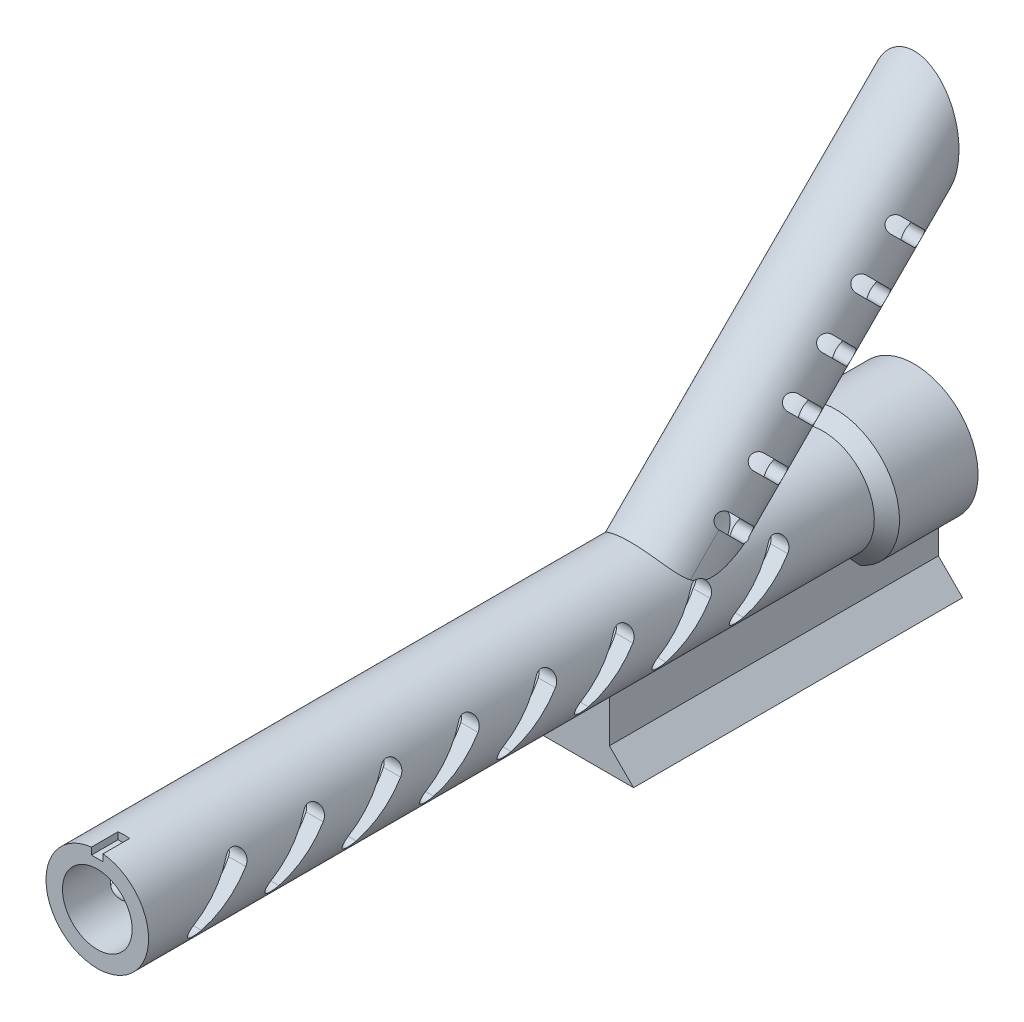
SolidWorks part; units mm, degrees
ref_plane "Front Plane" through (0, 0, 0) normal (0, 0, 1) x (1, 0, 0)
ref_plane "Top Plane" through (0, 0, 0) normal (0, 1, 0) x (1, 0, 0)
ref_plane "Right Plane" through (0, 0, 0) normal (1, 0, 0) x (0, 0, -1)
sketch "Esquisse3" plane through (0, 0, 0) normal (1, 0, 0) x (0, 0, -1)
  line L0 (-115.2452, 0) -> (50.9996, 0) construction
  line L1 (-0.8426, 10.6) -> (-150.8426, 10.6)
  line L2 (0, 7.2) -> (-150.8426, 7.2)
  line L3 (-150.8426, 10.6) -> (-150.8426, 7.2)
  line L4 (-0.8426, 10.6) -> (1.7574, 13.2)
  line L5 (0, 7.2) -> (3, 10.2)
  line L6 (1.7574, 13.2) -> (18, 13.2)
  line L7 (3, 10.2) -> (18, 10.2)
  line L8 (18, 13.2) -> (18, 10.2)
  dimension "D1" = 21.2
  dimension "D2" = 150
  dimension "D3" = 3
  dimension "D4" = 3
  dimension "D5" = 45
  dimension "D6" = 15
  dimension "D7" = 14.4
  dimension "D8" = 20.4
revolve "Révolution2" add sketch "Esquisse3" angle 360 about L0
sketch "Esquisse11" plane through (0, 0, 0) normal (1, 0, 0) x (0, 0, -1)
  line L0 (-27.5426, 10.6) -> (18.4193, 56.5619) construction
  line L1 (-0.8426, 10.6) -> (-150.8426, 10.6) construction
  dimension "D1" = 45
  dimension "D2" = 26.7
  dimension "D3" = 65
ref_plane "Plan1" through (0, 9, -9) normal (0, 0.7071, -0.7071) x (-1, 0, 0)
sketch "Esquisse12" plane through (0, 9, -9) normal (0, 0.7071, -0.7071) x (-1, 0, 0)
  circle A1 centre (0, 26.9709) radius 9.25
  dimension "D1" = 18.5
extrude "Boss.-Extru.2" add sketch "Esquisse12" against normal up to surface and the other way up to surface up to face at (10.6, 0, 150.8426) other way up to face at (13.2, 0, -18)
sketch "Esquisse16" plane through (0, 9, -9) normal (0, 0.7071, -0.7071) x (-1, 0, 0)
  circle A0 centre (0, 26.9709) radius 6.75
  circle A1 centre (0, 26.9709) radius 9.25 construction
  dimension "D1" = 2.5
extrude "Enlèv. mat.-Extru.4" cut sketch "Esquisse16" against normal up to next and the other way up to next
sketch "Esquisse4" plane through (0, 0, 0) normal (1, 0, 0) x (0, 0, -1)
  line L0 (-139.8426, -4) -> (-131.8426, 4) construction
  line L1 (-141.2569, -2.5858) -> (-133.2569, 5.4142)
  line L2 (-138.4284, -5.4142) -> (-130.4284, 2.5858)
  line L3 (-150.8426, 10.6) -> (-150.8426, -10.6) construction
  line L4 (-150.8426, -10.6) -> (-0.8426, -10.6) construction
  arc A0 (-141.2569, -2.5858) -> (-138.4284, -5.4142) centre (-139.8426, -4) ccw
  arc A1 (-130.4284, 2.5858) -> (-133.2569, 5.4142) centre (-131.8426, 4) ccw
  point P2 (-135.8426, 0)
  dimension "D1" = 8
  dimension "D2" = 45
  dimension "D3" = 4
  dimension "D4" = 15
extrude "Enlèv. mat.-Extru.1" cut sketch "Esquisse4" against normal through all both and the other way through all
pattern_linear "Répétition linéaire1" count 8 spacing 16 along (0, 0, -1) of "Enlèv. mat.-Extru.1"
sketch "Esquisse5" plane through (0, 0, 150.8426) normal (0, 0, 1) x (1, 0, 0)
  line L1 (1.2, 10.6) -> (-1.2, 10.6)
  line L2 (1.2, 10.6) -> (1.2, 9.1)
  line L3 (1.2, 9.1) -> (-1.2, 9.1)
  line L4 (-1.2, 10.6) -> (-1.2, 9.1)
  line L5 (1.2, 10.6) -> (-1.2, 9.1) construction
  line L6 (1.2, 9.1) -> (-1.2, 10.6) construction
  line L7 (-1, 9.3) -> (-1, 10.7536) construction
  line L8 (1, 9.3) -> (-1, 9.3) construction
  circle A0 centre (0, 0) radius 10.6 construction
  point P0 (0, 9.85)
  dimension "D1" = 0.2
  dimension "D2" = 0.2
extrude "Enlèv. mat.-Extru.2" cut sketch "Esquisse5" against normal blind 5.5
sketch "Esquisse13" plane through (0, 0, 0) normal (1, 0, 0) x (0, 0, -1)
  line L0 (10.4749, 43.6678) -> (5.5251, 48.6175) construction
  line L1 (9.4142, 42.6071) -> (4.4645, 47.5569)
  line L2 (11.5355, 44.7284) -> (6.5858, 49.6782)
  line L4 (-27.5426, 10.6) -> (18.4193, 56.5619) construction
  line L5 (18, 43.0612) -> (18, 69.2241) construction
  arc A0 (9.4142, 42.6071) -> (11.5355, 44.7284) centre (10.4749, 43.6678) ccw
  arc A1 (6.5858, 49.6782) -> (4.4645, 47.5569) centre (5.5251, 48.6175) ccw
  point P2 (8, 46.1426)
  dimension "D1" = 3
  dimension "D2" = 7
  dimension "D3" = 10
extrude "Enlèv. mat.-Extru.3" cut sketch "Esquisse13" against normal through all both and the other way through all
pattern_linear "Répétition linéaire2" count 6 spacing 10 along (0, -0.7071, 0.7071) of "Enlèv. mat.-Extru.3"
sketch "Esquisse14" plane through (0, 0, 0) normal (0, 0, -1) x (-1, 0, 0)
  line L0 (-5, -18.6603) -> (-10, -23.6603)
  line L1 (-10, -23.6603) -> (10, -23.6603)
  line L2 (10, -23.6603) -> (5, -18.6603)
  line L5 (-5, -18.6603) -> (-5, -9.3467)
  line L6 (5, -18.6603) -> (5, -9.3467)
  arc A1 (5, -9.3467) -> (-5, -9.3467) centre (0, 0) cw
  arc A2 (-1.2, 10.5319) -> (1.2, 10.5319) centre (0, 0) ccw construction
  point P16 (0, -23.6603)
  dimension "D1" = 45
  dimension "D2" = 10
extrude "Boss.-Extru.3" add sketch "Esquisse14" against normal blind 50 and the other way up to surface other way up to face at (13.2, 0, -18)
sketch "Esquisse17" plane through (0, -23.6603, 0) normal (0, -1, 0) x (-1, 0, 0)
  line L1 (2.7, 4.5) -> (-2.7, 4.5)
  line L2 (2.7, 4.5) -> (2.7, 1.1)
  line L3 (2.7, 1.1) -> (-2.7, 1.1)
  line L4 (-2.7, 4.5) -> (-2.7, 1.1)
  dimension "D1" = 3.4
  dimension "D2" = 5.4
extrude "Enlèv. mat.-Extru.5" cut sketch "Esquisse17" against normal blind 5
